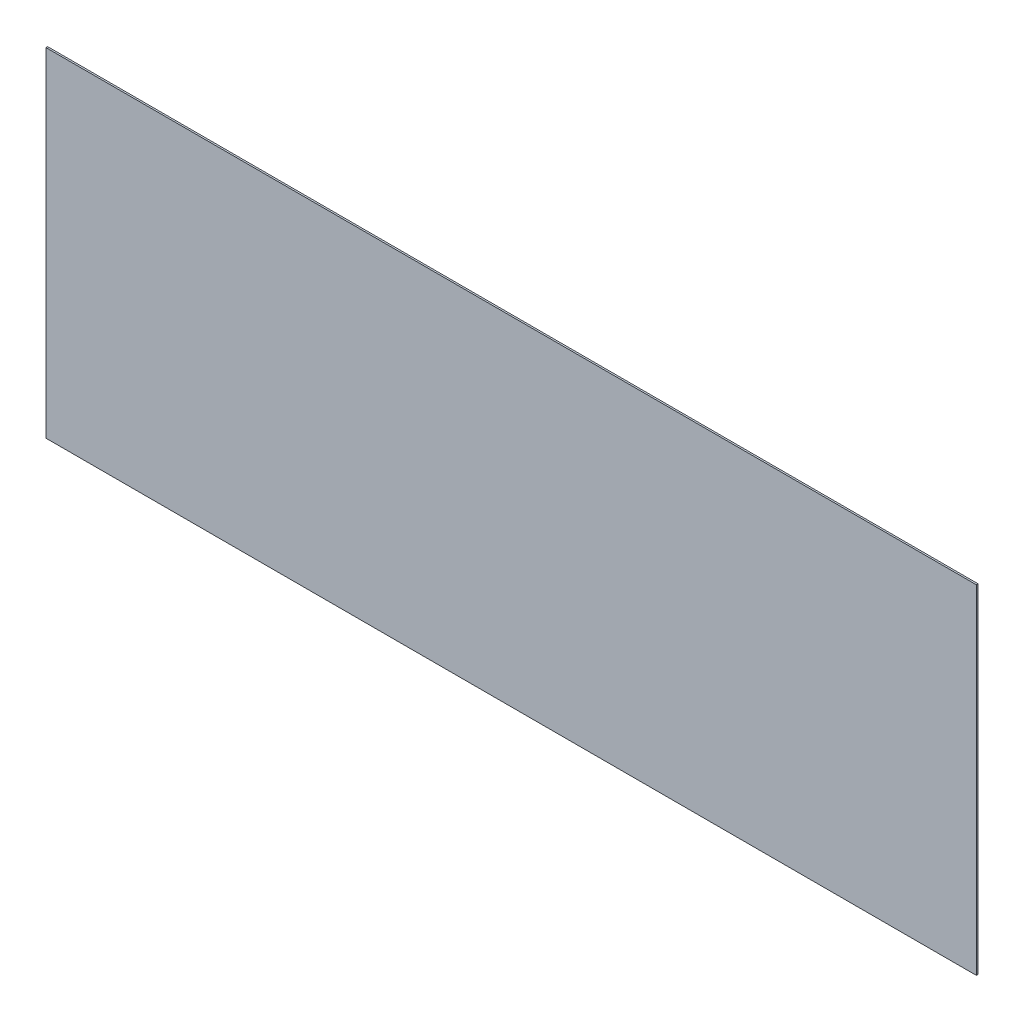
SolidWorks part; units mm, degrees
ref_plane "Front Plane" through (0, 0, 0) normal (0, 0, 1) x (1, 0, 0)
ref_plane "Top Plane" through (0, 0, 0) normal (0, 1, 0) x (1, 0, 0)
ref_plane "Right Plane" through (0, 0, 0) normal (1, 0, 0) x (0, 0, -1)
sketch "Sketch1" plane through (0, 0, 0) normal (0, 0, 1) x (1, 0, 0)
  line L1 (2750, 1000) -> (-2750, 1000)
  line L2 (2750, 1000) -> (2750, -1000)
  line L3 (2750, -1000) -> (-2750, -1000)
  line L4 (-2750, 1000) -> (-2750, -1000)
  line L5 (2750, 1000) -> (-2750, -1000) construction
  line L6 (2750, -1000) -> (-2750, 1000) construction
  point P0 (0, 0)
  dimension "D1" = 2000
  dimension "D2" = 5500
extrude "Boss-Extrude1" add sketch "Sketch1" along normal mid plane 10
